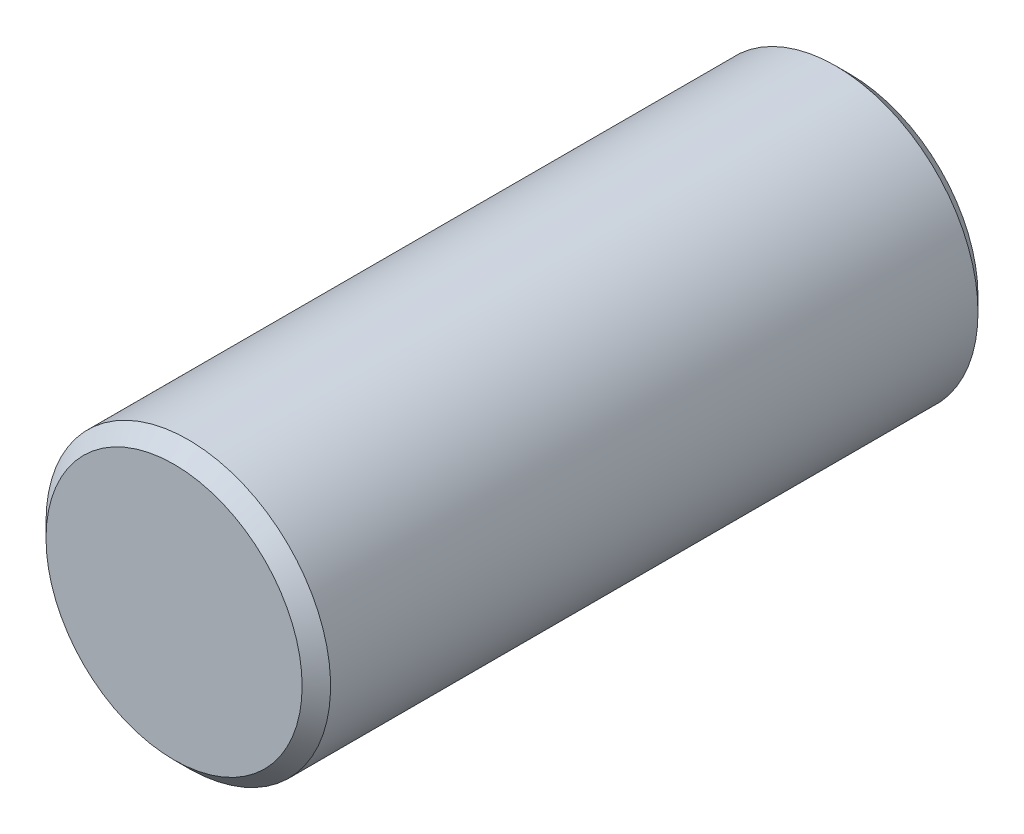
SolidWorks part; units mm, degrees
ref_plane "Front Plane" through (0, 0, 0) normal (0, 0, 1) x (1, 0, 0)
ref_plane "Top Plane" through (0, 0, 0) normal (0, 1, 0) x (1, 0, 0)
ref_plane "Right Plane" through (0, 0, 0) normal (1, 0, 0) x (0, 0, -1)
sketch "Sketch1" plane through (0, 0, 0) normal (0, 0, 1) x (1, 0, 0)
  circle A0 centre (0, 0) radius 12.7
  dimension "D1" = 25.4
extrude "Boss-Extrude1" add sketch "Sketch1" along normal blind 60.325
chamfer "Chamfer1" distance 1.27 angle 45 2 edges at (12.7, 0, 60.325) (12.7, 0, 0)
